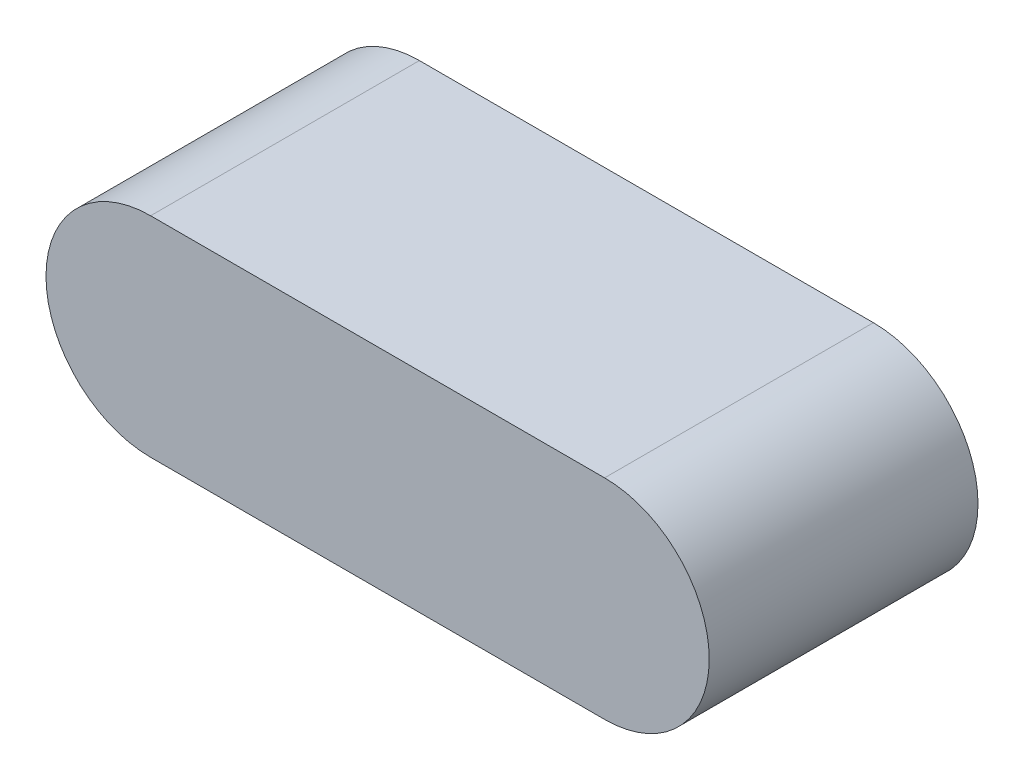
SolidWorks part; units mm, degrees
ref_plane "前视基准面" through (0, 0, 0) normal (0, 0, 1) x (1, 0, 0)
ref_plane "上视基准面" through (0, 0, 0) normal (0, 1, 0) x (1, 0, 0)
ref_plane "右视基准面" through (0, 0, 0) normal (1, 0, 0) x (0, 0, -1)
sketch "Sketch1" plane through (0, 0, 0) normal (0, 0, 1) x (1, 0, 0)
  line L0 (0, 0) -> (84.4516, 0) construction
  line L1 (0, 19.4583) -> (84.4516, 19.4583)
  line L2 (0, -19.4583) -> (84.4516, -19.4583)
  arc A0 (0, 19.4583) -> (0, -19.4583) centre (0, 0) ccw
  arc A1 (84.4516, -19.4583) -> (84.4516, 19.4583) centre (84.4516, 0) ccw
  point P3 (42.2258, 0)
extrude "Boss-Extrude1" add sketch "Sketch1" against normal blind 20 from offset 20
sketch "Sketch2" plane through (0, 0, 20) normal (0, 0, 1) x (1, 0, 0)
  line L2 (0, -19.4583) -> (84.4516, -19.4583)
  line L3 (84.4516, 19.4583) -> (0, 19.4583)
  line L4 (0, -19.4583) -> (84.4516, -19.4583)
  line L5 (84.4516, 19.4583) -> (0, 19.4583)
  arc A2 (0, 19.4583) -> (0, -19.4583) centre (0, 0) ccw
  arc A3 (84.4516, -19.4583) -> (84.4516, 19.4583) centre (84.4516, 0) ccw
  arc A4 (0, 19.4583) -> (0, -19.4583) centre (0, 0) ccw
  arc A5 (84.4516, -19.4583) -> (84.4516, 19.4583) centre (84.4516, 0) ccw
  dimension "D1" = 0
extrude "Boss-Extrude2" add sketch "Sketch2" against normal up to surface (30 mm away) from offset 30 contours A4 L4 A5 L5
